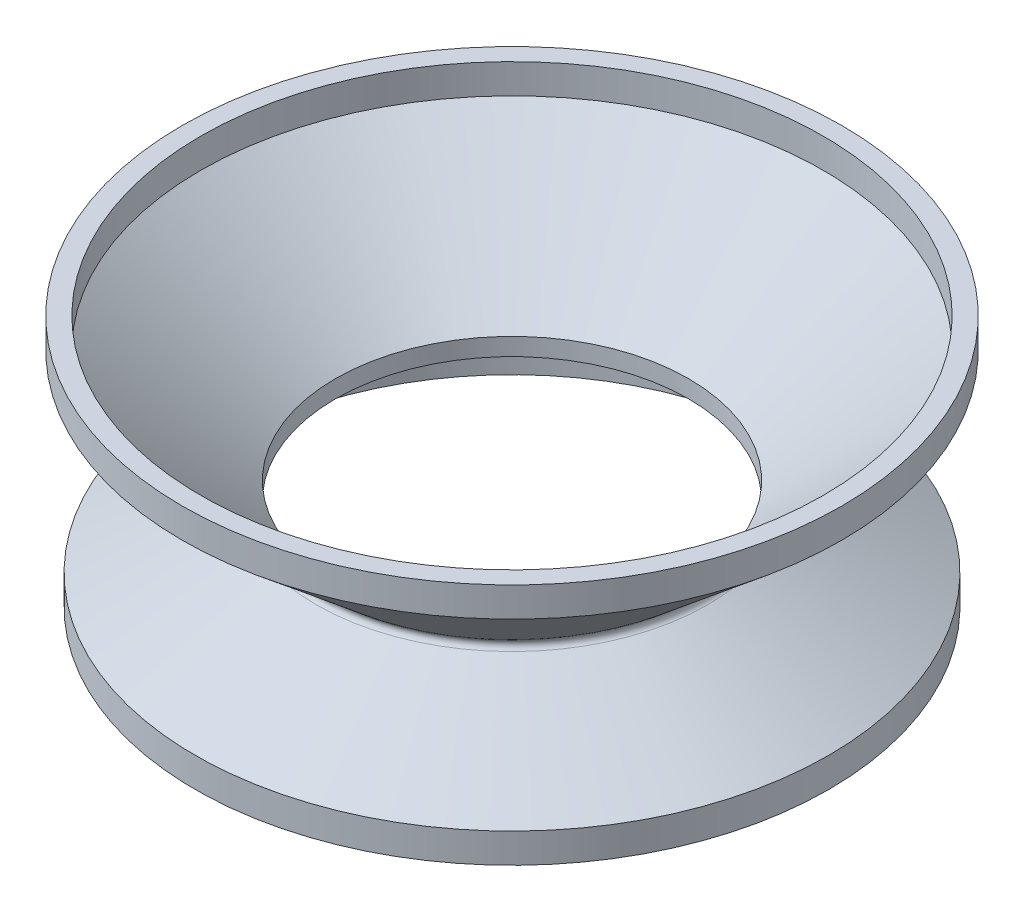
SolidWorks part; units mm, degrees
ref_plane "Front Plane" through (0, 0, 0) normal (0, 0, 1) x (1, 0, 0)
ref_plane "Top Plane" through (0, 0, 0) normal (0, 1, 0) x (1, 0, 0)
ref_plane "Right Plane" through (0, 0, 0) normal (1, 0, 0) x (0, 0, -1)
sketch "Sketch1" plane through (0, 0, 0) normal (0, 0, 1) x (1, 0, 0)
  line L0 (-42.6436, 0) -> (43.9692, 0) construction
  line L1 (0.6628, 0) -> (-8.8712, 8)
  line L2 (0.6628, 0) -> (-7.9975, -5)
  line L3 (1.4628, -0.8083) -> (-5.7975, -5)
  line L5 (-8.8712, 8) -> (-7.6267, 8)
  line L6 (-7.9975, -5) -> (-5.7975, -5)
  line L7 (13.3733, 7.609) -> (13.3733, -7.609) construction
  line L8 (2.5733, -0.1671) -> (-16.3192, 15.6855) construction
  line L9 (0.6628, 0) -> (-17.0263, 14.8429) construction
  line L10 (0.6628, 0) -> (-17.9865, -10.7671) construction
  line L11 (2.5733, -0.1671) -> (-17.4365, -11.7198) construction
  line L12 (0.6628, 0) -> (2.2628, 0) construction
  line L13 (1.4628, -0.8083) -> (1.4628, 0.373)
  line L14 (1.4628, 0.373) -> (-7.6267, 8)
  point P11 (1.4628, 0)
  dimension "D1" = 40
  dimension "D2" = 30
  dimension "D4" = 8
  dimension "D5" = 5
  dimension "D6" = 21
  dimension "D7" = 1.6
  dimension "D8" = 0.8
  dimension "D3" = 1.1
revolve "Revolve1" add sketch "Sketch1" angle 360 about L7
scale "Scale1" [suppressed]
fillet "Fillet2" radius 0.4 1 edges at (0.6628, 0, 0)
sketch "Sketch2" plane through (0, 8, 0) normal (0, 1, 0) x (1, 0, 0)
  circle A0 centre (13.3733, 0) radius 22.2446 construction
  circle A1 centre (13.3733, 0) radius 21 construction
  circle A2 centre (13.3733, 0) radius 22.2446
  circle A3 centre (13.3733, 0) radius 21
extrude "Boss-Extrude1" add sketch "Sketch2" along normal blind 2
sketch "Sketch3" plane through (0, -5, 0) normal (0, -1, 0) x (1, 0, 0)
  circle A0 centre (13.3733, 0) radius 19.1708 construction
  circle A1 centre (13.3733, 0) radius 21.3708 construction
  circle A2 centre (13.3733, 0) radius 19.1708
  circle A3 centre (13.3733, 0) radius 21.3708
extrude "Boss-Extrude2" add sketch "Sketch3" along normal blind 2
